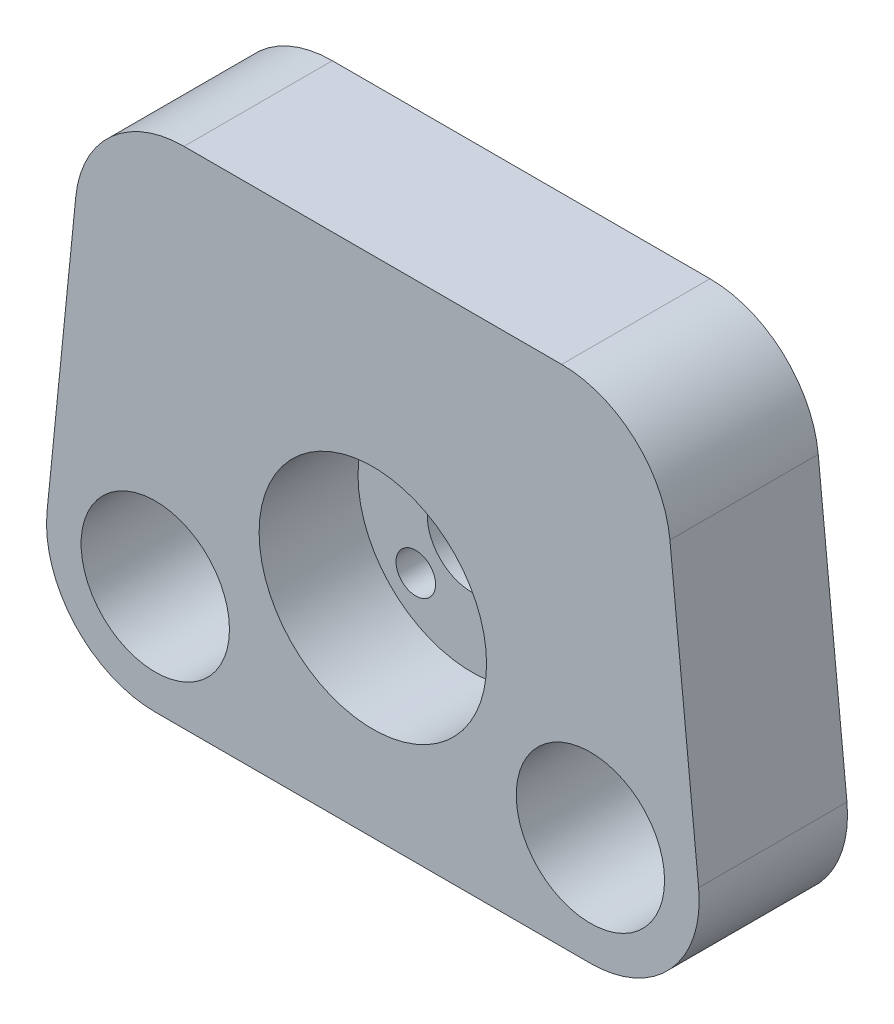
SolidWorks part; units mm, degrees
ref_plane "Front Plane" through (0, 0, 0) normal (0, 0, 1) x (1, 0, 0)
ref_plane "Top Plane" through (0, 0, 0) normal (0, 1, 0) x (1, 0, 0)
ref_plane "Right Plane" through (0, 0, 0) normal (1, 0, 0) x (0, 0, -1)
sketch "PosicionAgujeros" plane through (0, 0, 0) normal (0, 0, 1) x (1, 0, 0)
  line L0 (-18.25, 0) -> (18.25, 0) construction
  line L3 (22, -10) -> (-22, -10) construction
  line L7 (0, 0) -> (0, 20) construction
  line L8 (-20, 20) -> (20, 20) construction
  line L9 (0, 0) -> (5.6569, 5.6569) construction
  circle A1 centre (22, -10) radius 4 construction
  circle A2 centre (18.25, 0) radius 2.5 construction
  circle A3 centre (0, 0) radius 4 construction
  circle A4 centre (0, 0) radius 8 construction
  circle A6 centre (0, 0) radius 11 construction
  circle A7 centre (-20, 20) radius 10 construction
  circle A8 centre (20, 20) radius 10 construction
  point P2 (0, 0)
  point P8 (22, -10)
  point P9 (-18.25, 0)
  point P10 (18.25, 0)
  point P11 (0, -10)
  point P18 (-22, -10)
  point P24 (5.6569, 5.6569)
  point P26 (0, 20)
  dimension "D4" = 8
  dimension "D5" = 5
  dimension "D6" = 8
  dimension "D7" = 16
  dimension "D8" = 40
  dimension "D10" = 22
  dimension "D13" = 20
  dimension "D14" = 20
  dimension "D1" = 36.5
  dimension "D2" = 44
  dimension "D3" = 10
  dimension "D9" = 20
  dimension "D11" = 45
sketch "Croquis2" plane through (0, 0, 0) normal (0, 0, 1) x (1, 0, 0)
  line L0 (0, 0) -> (0, 20) construction
  line L1 (-34.1569, -21) -> (34.1569, -21)
  line L2 (-34.1569, -21) -> (-29.0484, 30)
  line L3 (-29.0484, 30) -> (29.0484, 30)
  line L4 (34.1569, -21) -> (29.0484, 30)
  line L5 (-34.1569, -21) -> (29.0484, 30) construction
  line L6 (-29.0484, 30) -> (34.1569, -21) construction
  circle A0 centre (22, -10) radius 7.5
  circle A2 centre (-22, -10) radius 7.5
  circle A4 centre (-20, 20) radius 10 construction
  circle A5 centre (-22, -10) radius 11 construction
  circle A6 centre (22, -10) radius 11 construction
  circle A9 centre (0, 0) radius 4.5
  point P3 (0, 6.561)
  dimension "D1" = 15
  dimension "D3" = 15
  dimension "D2" = 22
  dimension "D4" = 22
  dimension "D5" = 9
extrude "Saliente-Extruir1" add sketch "Croquis2" along normal blind 15
fillet "Redondeo2" radius 11 4 edges at (34.1569, -21, 7.5) (-34.1569, -21, 7.5) (29.0484, 30, 7.5) (-29.0484, 30, 7.5)
sketch "Croquis4" plane through (0, 0, 15) normal (0, 0, 1) x (1, 0, 0)
  circle A0 centre (0, 0) radius 11.5
  dimension "D1" = 23
extrude "Cortar-Extruir1" cut sketch "Croquis4" against normal blind 10
hole_wizard "Taladro de margen para M31" positions "Croquis14" profile "Croquis16" hole size "M3" standard "DIN" end condition through all
sketch "Croquis14" plane through (0, 0, 0) normal (0, 0, -1) x (-1, 0, 0)
  point P0 (-5.6569, 5.6569)
sketch "Croquis16" plane through (5.6569, 5.6569, 0) normal (1, 0, 0) x (0, 1, 0)
  line L0 (0, 0) -> (0, 15)
  line L1 (0, 15) -> (2, 15)
  line L2 (2, 15) -> (2, 0)
  line L5 (2, 0) -> (0, 0)
  line L11 (0, -6.35) -> (0, 107.95) construction
  dimension "Diámetro de taladro hasta el siguiente" = 4
  dimension "Profundidad de taladro hasta el siguiente" = 15
pattern_circular "MatrizC1" count 4 over 360 about axis through (0, 0, 0) along (0, 0, 1) of "Taladro de margen para M31"
sketch "Croquis17" plane through (0, 0, 0) normal (0, 0, 1) x (1, 0, 0)
  circle A8 centre (0, 20) radius 5
  point P1 (21.3832, -8.0688)
  point P8 (0, 20)
  dimension "D2" = 10
equation "\"D3@Croquis2\"=\"D1@Croquis2\""
